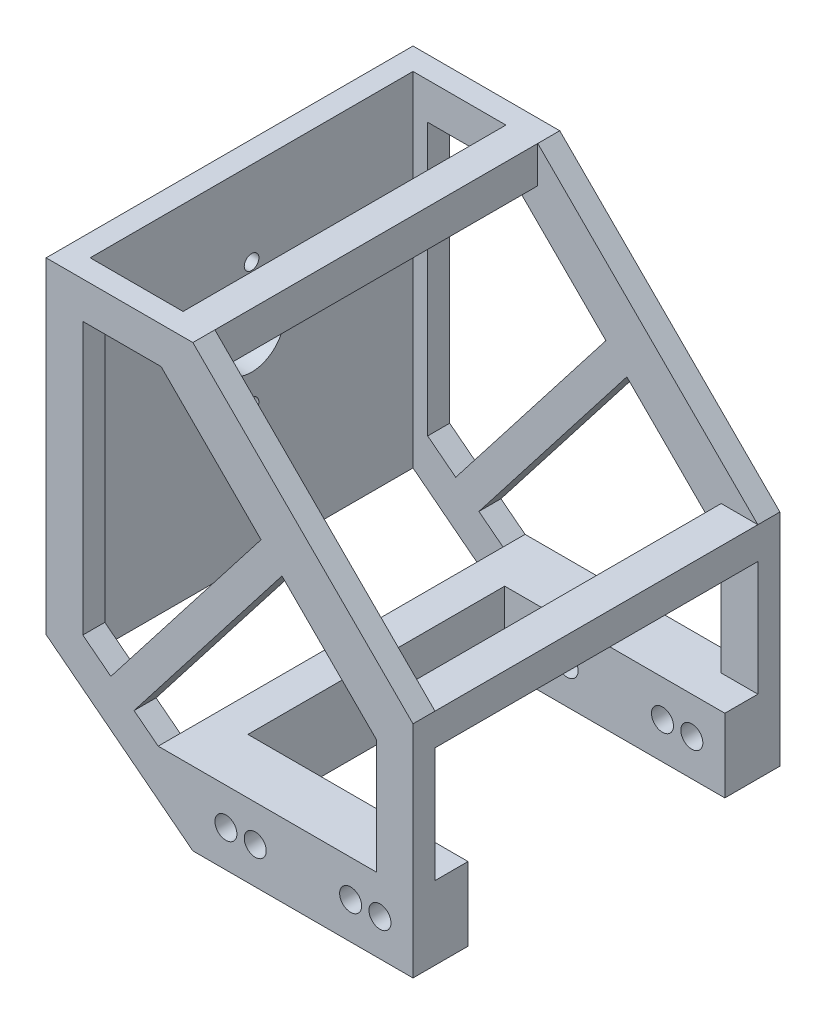
SolidWorks part; units mm, degrees
ref_plane "Front Plane" through (0, 0, 0) normal (0, 0, 1) x (1, 0, 0)
ref_plane "Top Plane" through (0, 0, 0) normal (0, 1, 0) x (1, 0, 0)
ref_plane "Right Plane" through (0, 0, 0) normal (1, 0, 0) x (0, 0, -1)
sketch "Sketch2" plane through (0, 0, 0) normal (0, 0, 1) x (1, 0, 0)
  line L1 (0, 20) -> (50, 20)
  line L2 (0, 20) -> (0, -40)
  line L3 (0, -40) -> (50, -40)
  line L4 (50, 20) -> (50, -40)
  dimension "D1" = 50
  dimension "D2" = 60
  dimension "D3" = 20
extrude "Boss-Extrude1" add sketch "Sketch2" along normal mid plane 50
shell "Shell1" thickness 3
sketch "Sketch3" plane through (0, 0, 0) normal (-1, 0, 0) x (0, 0, 1)
  circle A0 centre (0, 0) radius 11
  dimension "D1" = 22
extrude "Boss-Extrude2" add sketch "Sketch3" along normal blind 3
sketch "Sketch4" plane through (-3, 0, 0) normal (-1, 0, 0) x (0, 0, 1)
  circle A0 centre (0, 0) radius 4.5
  circle A1 centre (-8.5, 0) radius 1
  circle A2 centre (0, 8.5) radius 1
  circle A3 centre (8.5, 0) radius 1
  circle A4 centre (0, -8.5) radius 1
  point P14 (0, 0)
  dimension "D1" = 8.5
  dimension "D2" = 9
  dimension "D3" = 2
  dimension "D4" = 4
extrude "Cut-Extrude1" cut sketch "Sketch4" against normal up to surface (6 mm away) up to face at (3, -10, 0)
sketch "Sketch5" plane through (0, 0, 25) normal (0, 0, 1) x (1, 0, 0)
  line L0 (0, -24.4726) -> (0, -40)
  line L1 (0, -40) -> (50, -40) construction
  line L2 (20, -40) -> (0, -24.4726)
  line L3 (0, 20) -> (0, -40) construction
  line L4 (0, -40) -> (20, -40)
  line L5 (20, 20) -> (50, -10)
  line L6 (50, 20) -> (0, 20) construction
  line L7 (50, -40) -> (50, 20) construction
  line L8 (50, -10) -> (50, 20)
  line L9 (50, 20) -> (20, 20)
  dimension "D1" = 30
  dimension "D2" = 30
  dimension "D3" = 30
extrude "Cut-Extrude2" cut sketch "Sketch5" against normal up to surface (50 mm away) up to face at (25, -10, -25)
sketch "Sketch6" plane through (0, 0, 25) normal (0, 0, 1) x (1, 0, 0)
  line L0 (5, 15) -> (15.6633, 15)
  line L1 (15.6633, 15) -> (45, -14.3367)
  line L2 (45, -14.3367) -> (45, -30)
  line L3 (45, -30) -> (15.2729, -30)
  line L4 (15.2729, -30) -> (5, -22.0244)
  line L5 (5, -22.0244) -> (5, 15)
  line L6 (20, 20) -> (0, 20) construction
  line L7 (0, 11) -> (0, -11) construction
  line L8 (20, -40) -> (0, -24.4726) construction
  line L9 (20, -40) -> (50, -40) construction
  line L10 (50, -40) -> (50, -10) construction
  line L11 (20, 20) -> (50, -10) construction
  point P8 (10, 20)
  dimension "D1" = 5
  dimension "D2" = 5
  dimension "D3" = 5
  dimension "D4" = 10
  dimension "D5" = 5
extrude "Cut-Extrude4" cut sketch "Sketch6" against normal up to surface (50 mm away) up to face at (23.3333, -12.4121, -25)
sketch "Sketch7" plane through (0, 0, 22) normal (0, 0, -1) x (-1, 0, 0)
  line L0 (-5, -22.0244) -> (-15.2729, -30) construction
  line L1 (-20, 20) -> (-15.6633, 20)
  line L2 (-20, 20) -> (-20, 15)
  line L3 (-20, 15) -> (-15.6633, 15)
  line L4 (-15.6633, 20) -> (-15.6633, 15)
  line L5 (-50, -10) -> (-45, -10)
  line L6 (-50, -10) -> (-50, -14.3367)
  line L7 (-50, -14.3367) -> (-45, -14.3367)
  line L8 (-45, -10) -> (-45, -14.3367)
  line L9 (-15.2729, -30) -> (-20, -30)
  line L10 (-15.2729, -30) -> (-15.2729, -36.33)
  line L12 (-20, -30) -> (-20, -40)
  line L13 (-15.2729, -30) -> (-45, -30) construction
  line L14 (-20, -40) -> (-15.2729, -36.33)
  line L15 (-20, -40) -> (-3, -26.8017) construction
extrude "Boss-Extrude3" add sketch "Sketch7" along normal up to surface (44 mm away) up to face at (21.8227, -11.0602, -22)
sketch "Sketch8" plane through (-8.7882, -11.3197, 0) normal (0.6132, 0.7899, 0) x (0.7899, -0.6132, 0)
  line L0 (30.4613, 25) -> (17.4559, 25) construction
  line L1 (22.2949, 25) -> (26.2949, 25)
  line L2 (22.2949, 25) -> (22.2949, 22)
  line L3 (22.2949, 22) -> (26.2949, 22)
  line L4 (26.2949, 25) -> (26.2949, 22)
  line L5 (17.4559, 22) -> (30.4613, 22) construction
  line L6 (17.4559, -22) -> (30.4613, -22) construction
  line L7 (22.2949, -22) -> (26.2949, -22)
  line L8 (22.2949, -22) -> (22.2949, -25)
  line L9 (22.2949, -25) -> (26.2949, -25)
  line L10 (26.2949, -22) -> (26.2949, -25)
  line L11 (17.4559, -25) -> (30.4613, -25) construction
  dimension "D1" = 4
  dimension "D2" = 4
extrude "Boss-Extrude4" add sketch "Sketch8" along normal up to surface (32.8738 mm away)
sketch "Sketch10" plane through (0, 0, -22) normal (0, 0, 1) x (1, 0, 0)
  line L1 (20, -30) -> (50, -30)
  line L2 (20, -30) -> (20, -40)
  line L3 (20, -40) -> (50, -40)
  line L4 (50, -30) -> (50, -40)
extrude "Boss-Extrude5" add sketch "Sketch10" along normal blind 4.5
mirror "Mirror1" about plane through (0, 0, 0) normal (0, 0, 1) of "Boss-Extrude5"
sketch "Sketch9" plane through (0, 0, 25) normal (0, 0, 1) x (1, 0, 0)
  line L0 (20, -40) -> (50, -40) construction
  line L1 (15.2729, -30) -> (45, -30) construction
  circle A0 centre (24.5, -35) radius 1.5
  circle A1 centre (28.5, -35) radius 1.5
  circle A2 centre (41.5, -35) radius 1.5
  circle A3 centre (45.5, -35) radius 1.5
  point P10 (35, -40)
  dimension "D1" = 3
  dimension "D2" = 3
  dimension "D3" = 3
  dimension "D4" = 3
  dimension "D5" = 13
  dimension "D6" = 21
  dimension "D7" = 4
  dimension "D9" = 5
  dimension "D10" = 5
  dimension "D11" = 5
  dimension "D8" = 10.5
extrude "Cut-Extrude5" cut sketch "Sketch9" against normal up to surface (50 mm away)
